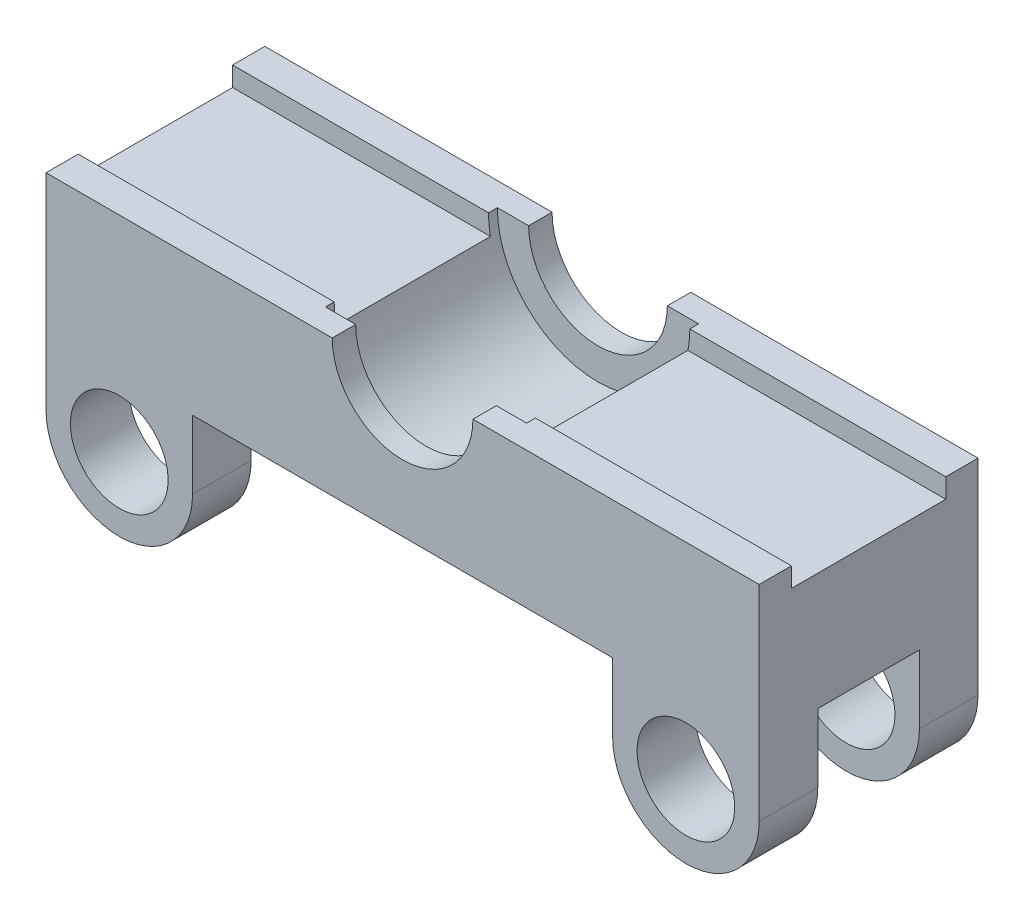
SolidWorks part; units mm, degrees
ref_plane "Plan de face" through (0, 0, 0) normal (0, 0, 1) x (1, 0, 0)
ref_plane "Plan de dessus" through (0, 0, 0) normal (0, 1, 0) x (1, 0, 0)
ref_plane "Plan de droite" through (0, 0, 0) normal (1, 0, 0) x (0, 0, -1)
sketch "Esquisse1" plane through (0, 0, 0) normal (0, 0, 1) x (1, 0, 0)
  line L1 (36.5, 0) -> (36.5, -7)
  line L2 (36.5, -7) -> (0, -7)
  line L3 (0, -7) -> (0, 0)
  line L5 (0, 0) -> (36.5, 0)
  dimension "D1" = 0
  dimension "D2" = 36.5
  dimension "D3" = 7
extrude "Boss.-Extru.1" add sketch "Esquisse1" along normal blind 10
sketch "Esquisse2" plane through (0, 0, 10) normal (0, 0, 1) x (1, 0, 0)
  line L0 (36.5, 0) -> (0, 0) construction
  circle A0 centre (18.25, 0) radius 5.15
  dimension "D1" = 10.3
extrude "Enlèv. mat.-Extru.1" cut sketch "Esquisse2" against normal blind 10
sketch "Esquisse3" plane through (0, 0, 0) normal (-1, 0, 0) x (0, 0, 1)
  line L0 (10, 0) -> (0, 0) construction
  line L1 (0.45, 0) -> (8.35, 0)
  line L2 (0.45, 0) -> (0.45, -1)
  line L3 (0.45, -1) -> (8.35, -1)
  line L4 (8.35, 0) -> (8.35, -1)
  line L5 (10, 0) -> (10, -7) construction
  dimension "D1" = 1
  dimension "D2" = 1.65
  dimension "D3" = 0.45
extrude "Enlèv. mat.-Extru.2" cut sketch "Esquisse3" against normal blind 40
sketch "Esquisse5" plane through (0, 0, 0) normal (0, 0, -1) x (-1, 0, 0)
  line L1 (-36.5, -7) -> (0, -7)
  line L2 (-36.5, -7) -> (-36.5, 0)
  line L3 (-36.5, 0) -> (0, 0)
  line L4 (0, -7) -> (0, 0)
  dimension "D1" = 7
  dimension "D2" = 36.5
extrude "Boss.-Extru.2" add sketch "Esquisse5" along normal blind 1.2
sketch "Esquisse6" plane through (0, 0, -1.2) normal (0, 0, -1) x (-1, 0, 0)
  line L0 (0, 0) -> (-36.5, 0) construction
  circle A0 centre (-18.25, 0) radius 3.55
  dimension "D1" = 7.1
extrude "Enlèv. mat.-Extru.3" cut sketch "Esquisse6" against normal blind 10 contours A0
sketch "Esquisse8" plane through (0, 0, -1.2) normal (0, 0, -1) x (-1, 0, 0)
  line L1 (-36.5, -7) -> (-29, -7)
  line L2 (-36.5, -7) -> (-36.5, -10.5)
  line L4 (-29, -7) -> (-29, -10.5)
  arc A2 (-36.5, -10.5) -> (-29, -10.5) centre (-32.75, -10.5) ccw
  circle A3 centre (-32.75, -10.5) radius 2.5
  dimension "D4" = 5
  dimension "D1" = 7.5
  dimension "D2" = 3.5
  dimension "D3" = 3.5
extrude "Boss.-Extru.3" add sketch "Esquisse8" against normal blind 3
pattern_linear "Répétition linéaire1" count 2 spacing 8.2 along (0, 0, 1) count 2 spacing 29 along (-1, 0, 0) of "Boss.-Extru.3"
pattern_linear "Répétition linéaire2" count 2 spacing 10 along (0, 0, 1) of "Boss.-Extru.2"
sketch "Esquisse10" plane through (0, 0, 10) normal (0, 0, 1) x (1, 0, 0)
  line L0 (36.5, 0) -> (0, 0) construction
  circle A0 centre (18.25, 0) radius 3.6
  dimension "D1" = 7.2
extrude "Enlèv. mat.-Extru.4" cut sketch "Esquisse10" against normal blind 1.2
sketch "Esquisse11" plane through (0, -7, 0) normal (0, -1, 0) x (1, 0, 0)
  line L0 (7.5, 10) -> (29, 10) construction
  line L1 (8, 7.5) -> (11.5, 7.5)
  line L2 (8, 7.5) -> (8, 1.3)
  line L3 (8, 1.3) -> (11.5, 1.3)
  line L4 (11.5, 7.5) -> (11.5, 1.3)
  line L5 (29, -1.2) -> (7.5, -1.2) construction
  line L6 (0, 7) -> (0, 1.8) construction
  line L7 (36.5, 7) -> (36.5, 1.8) construction
  line L8 (25, 7.5) -> (28.5, 7.5)
  line L9 (25, 7.5) -> (25, 1.3)
  line L10 (25, 1.3) -> (28.5, 1.3)
  line L11 (28.5, 7.5) -> (28.5, 1.3)
  dimension "D1" = 2.5
  dimension "D2" = 2.5
  dimension "D3" = 8
  dimension "D4" = 3.5
  dimension "D5" = 3.5
  dimension "D6" = 2.5
  dimension "D7" = 2.5
  dimension "D8" = 8
extrude "Enlèv. mat.-Extru.5" cut sketch "Esquisse11" against normal blind 4
sketch "Esquisse15" plane through (0, 0, -1.2) normal (0, 0, -1) x (-1, 0, 0)
  line L1 (-8, -3) -> (-4.25, -3)
  line L2 (-8, -3) -> (-8, -5)
  line L3 (-8, -5) -> (-4.25, -5)
  line L4 (-4.25, -3) -> (-4.25, -5)
  line L6 (-28.5, -3) -> (-32.25, -3)
  line L7 (-28.5, -3) -> (-28.5, -5)
  line L8 (-28.5, -5) -> (-32.25, -5)
  line L9 (-32.25, -3) -> (-32.25, -5)
  dimension "D1" = 3.75
  dimension "D2" = 2
  dimension "D3" = 3.75
  dimension "D4" = 2
extrude "Enlèv. mat.-Extru.7" cut sketch "Esquisse15" against normal blind 5 from offset 2.5 offset against normal yes
sketch "Esquisse12" plane through (0, -7, 0) normal (0, -1, 0) x (-1, 0, 0)
  line L1 (-11.5, -7.5) -> (-25, -7.5)
  line L2 (-11.5, -7.5) -> (-11.5, -1.3)
  line L3 (-11.5, -1.3) -> (-25, -1.3)
  line L4 (-25, -7.5) -> (-25, -1.3)
extrude "Enlèv. mat.-Extru.6" cut sketch "Esquisse12" against normal blind 1
chamfer "Chanfrein1" distance 1.5 angle 45 4 edges at (28.5, -5, 3.8) (25, -6, 4.4) (11.5, -6, 4.4) (8, -5, 3.8)
